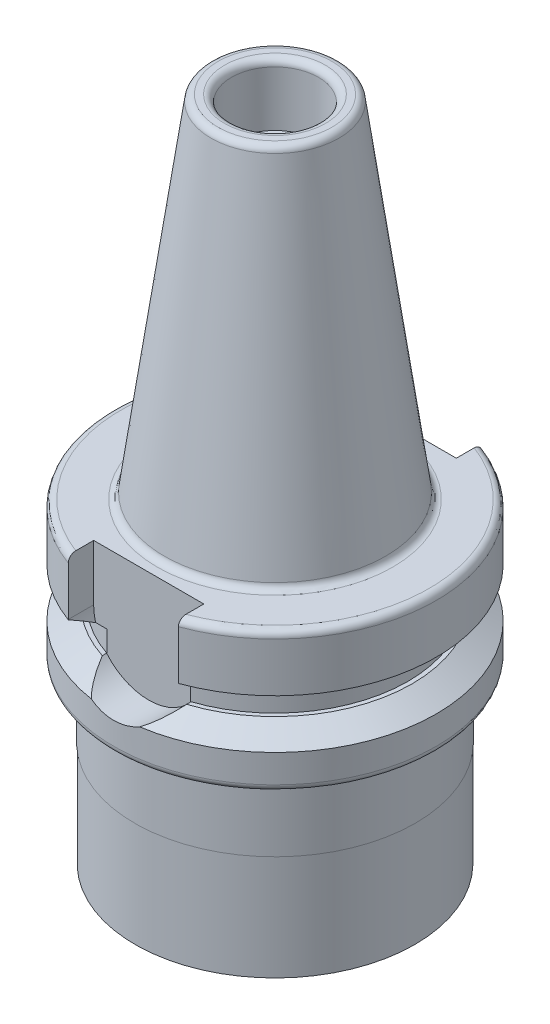
SolidWorks part; units mm, degrees
material "Plain Carbon Steel"
ref_plane "Front Plane" through (0, 0, 0) normal (0, 0, 1) x (1, 0, 0)
ref_plane "Top Plane" through (0, 0, 0) normal (0, 1, 0) x (1, 0, 0)
ref_plane "Right Plane" through (0, 0, 0) normal (1, 0, 0) x (0, 0, -1)
sketch "Sketch1" plane through (0, 0, 0) normal (0, 0, 1) x (1, 0, 0)
  line L0 (0, 0) -> (0, 75) construction
  line L1 (9, 70) -> (6.2, 70)
  line L2 (4, 61.15) -> (4, 9.2336)
  line L3 (15.275, -25) -> (19.945, -25)
  line L4 (0, 75) -> (0, 0) construction
  line L5 (9, 70) -> (15.9, 20)
  line L6 (15.9, 20) -> (23, 20)
  line L7 (23, 20) -> (23, 12)
  line L8 (23, 0) -> (20, 0)
  line L10 (23, 7) -> (23, 5) construction
  line L11 (23, 10) -> (19.56, 10) construction
  line L12 (23, 7) -> (19.56, 7) construction
  line L13 (18.96, 10) -> (18.96, 7)
  line L14 (6.2, 70) -> (6.2, 61.15)
  line L15 (6.2, 61.15) -> (4, 61.15)
  line L16 (0, 75) -> (0, 70) construction
  line L17 (0, 70) -> (6.2, 70) construction
  line L18 (19.56, 10) -> (23, 12)
  line L19 (19.56, 7) -> (23, 5)
  line L20 (23, 12) -> (23, 10) construction
  line L21 (19.56, 10) -> (18.96, 10)
  line L22 (19.56, 7) -> (18.96, 7)
  line L23 (23, 5) -> (23, 0)
  line L24 (4, 9.2336) -> (10.4638, 9.2336)
  line L25 (10.4638, 9.2336) -> (15.275, -25)
  line L30 (20, -10) -> (20, 0)
  line L31 (20, -10) -> (19.945, -10)
  line L33 (19.945, -10) -> (19.945, -25)
  dimension "D2" = 18
  dimension "D3" = 7
  dimension "D4" = 31.8
  dimension "D5" = 50
  dimension "D6" = 3
  dimension "D7" = 20
  dimension "D8" = 46
  dimension "D9" = 4.04
  dimension "D10" = 10
  dimension "D11" = 12.4
  dimension "D12" = 8.85
  dimension "D13" = 70
  dimension "D14" = 40
  dimension "D15" = 8
  dimension "D16" = 37.92
  dimension "D17" = 7
  dimension "D18" = 0.6
  dimension "D19" = 75
  dimension "D20" = 25
  dimension "D21" = 30.55
  dimension "D22" = 34.2336
  dimension "D23" = 39.89
  dimension "D24" = 15
  dimension "D25" = 8
revolve "Revolve1" add sketch "Sketch1" angle 360 about L0
fillet "Fillet1" radius 1 6 edges at (23, 20, 0) (15.9, 20, 0) (9, 70, 0) (6.2, 70, 0) (23, 0, 0) (20, 0, 0)
chamfer "Chamfer1" [suppressed] distance 3.5 angle 30
ref_plane "Plane1" through (0, 15.5, 23) normal (0, 0, 1) x (-1, 0, 0)
sketch "Sketch2" plane through (0, 15.5, 23) normal (0, 0, 1) x (-1, 0, 0)
  line L0 (0, -4.5) -> (0, 3.45) construction
  line L1 (-7.85, -4.5) -> (-7.85, 3.45)
  line L2 (7.85, -4.5) -> (7.85, 3.45)
  line L3 (22, 15.5) -> (-22, 15.5) construction
  line L4 (-22, -4.5) -> (22, -4.5) construction
  line L5 (-7.85, -4.5) -> (7.85, -4.5)
  arc A1 (7.85, 3.45) -> (-7.85, 3.45) centre (0, 3.45) ccw
  point P2 (0, -13.9248)
  dimension "D1" = 15.7
  dimension "D3" = 4.2
extrude "Extrude1" cut sketch "Sketch2" against normal blind 5
mirror "Mirror1" about plane through (0, 0, 0) normal (0, 0, 1) of "Extrude1"
